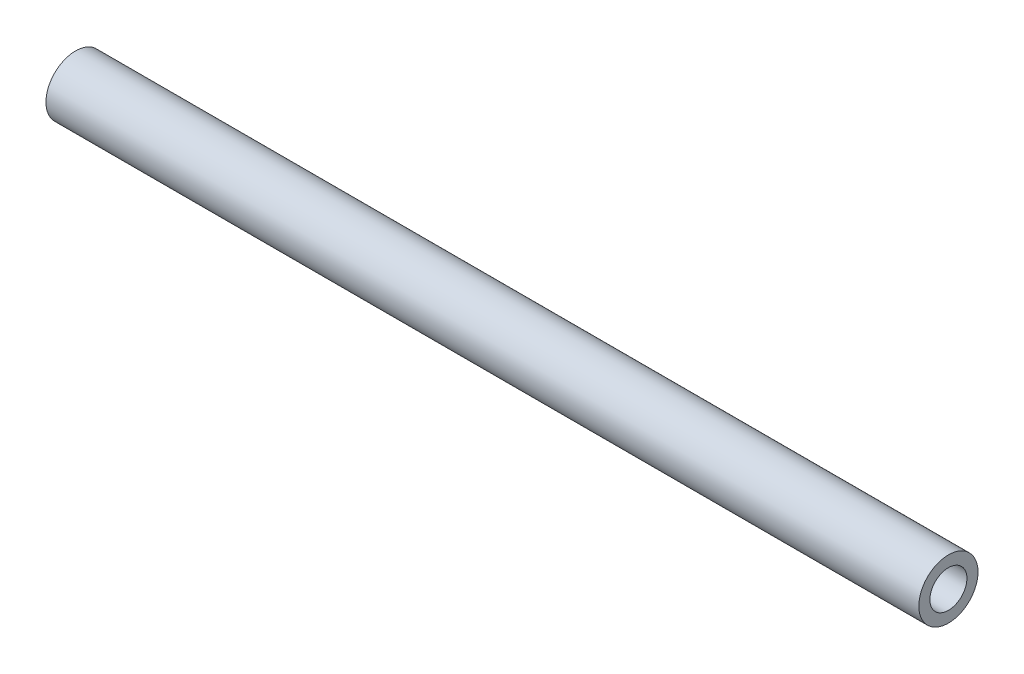
SolidWorks part; units mm, degrees
material "AISI 1045 Steel, cold drawn"
ref_plane "Front Plane" through (0, 0, 0) normal (1, 0, 0) x (0, 1, 0)
ref_plane "Top Plane" through (0, 0, 0) normal (0, 0, 1) x (0, 1, 0)
ref_plane "Right Plane" through (0, 0, 0) normal (0, 1, 0) x (-1, 0, 0)
sketch "Sketch2" plane through (0, 0, 0) normal (1, 0, 0) x (0, 1, 0)
  circle A0 centre (0, 0) radius 4
  circle A1 centre (0, 0) radius 2.5
  dimension "D1" = 8
  dimension "D2" = 5
extrude "Boss-Extrude1" add sketch "Sketch2" along normal blind 118
